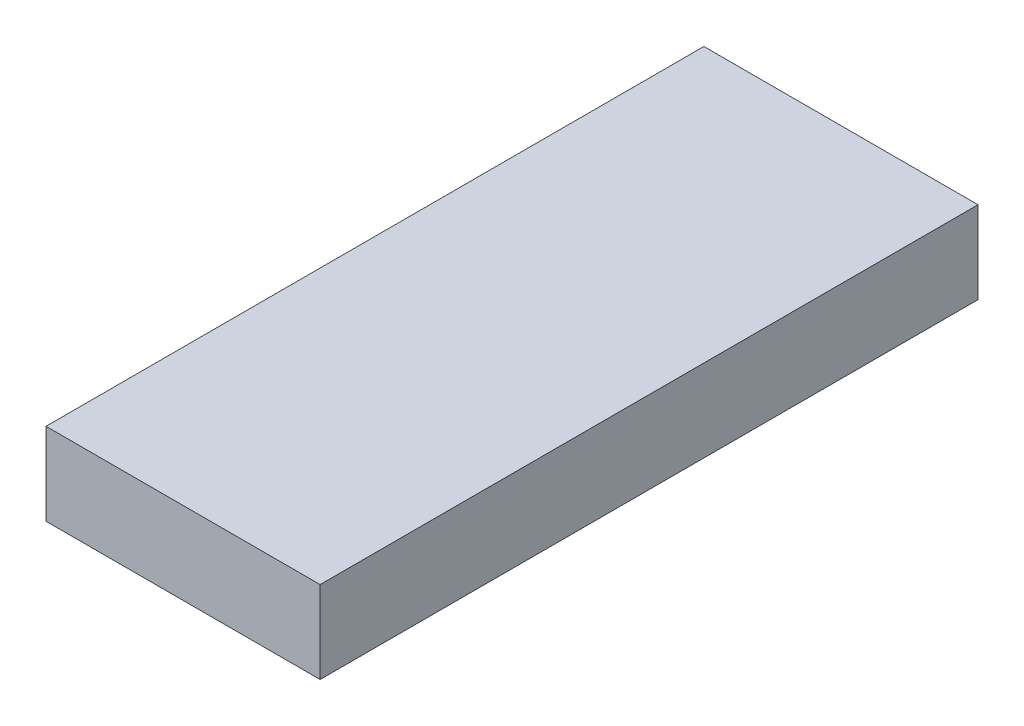
SolidWorks part; units mm, degrees
ref_plane "Front Plane" through (0, 0, 0) normal (0, 0, 1) x (1, 0, 0)
ref_plane "Top Plane" through (0, 0, 0) normal (0, 1, 0) x (1, 0, 0)
ref_plane "Right Plane" through (0, 0, 0) normal (1, 0, 0) x (0, 0, -1)
sketch "Sketch1" plane through (0, 0, 0) normal (0, 1, 0) x (1, 0, 0)
  line L1 (-25, -60) -> (25, -60)
  line L2 (-25, -60) -> (-25, 60)
  line L3 (-25, 60) -> (25, 60)
  line L4 (25, -60) -> (25, 60)
  line L5 (-25, -60) -> (25, 60) construction
  line L6 (-25, 60) -> (25, -60) construction
  point P0 (0, 0)
  dimension "D1" = 120
  dimension "D2" = 50
extrude "Boss-Extrude1" add sketch "Sketch1" along normal mid plane 15
